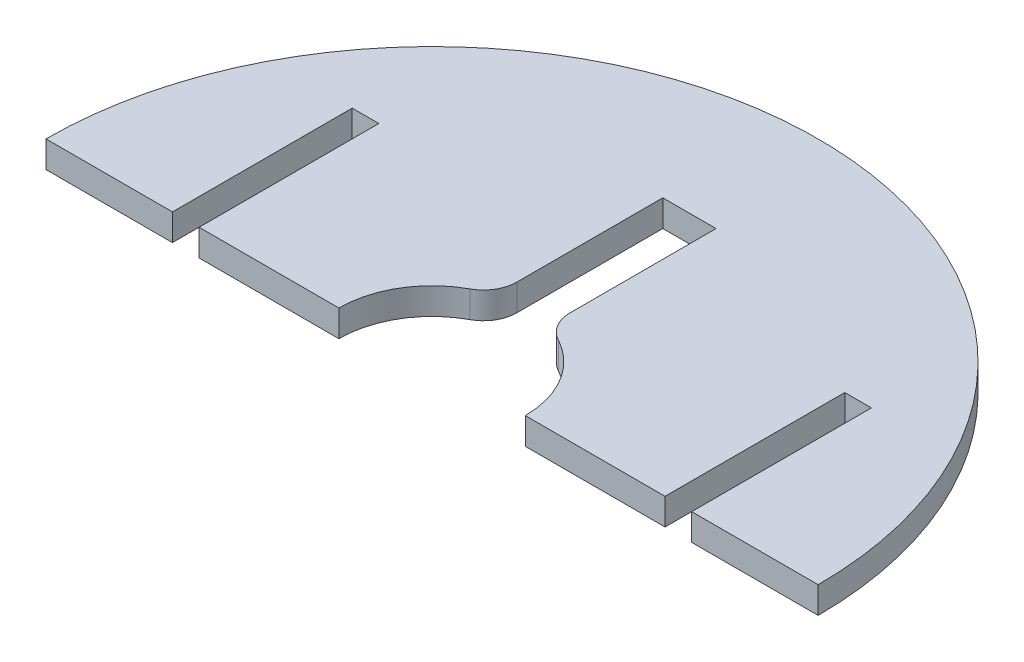
SolidWorks part; units mm, degrees
ref_plane "Front Plane" through (0, 0, 0) normal (0, 0, 1) x (1, 0, 0)
ref_plane "Top Plane" through (0, 0, 0) normal (0, 1, 0) x (1, 0, 0)
ref_plane "Right Plane" through (0, 0, 0) normal (1, 0, 0) x (0, 0, -1)
sketch "Sketch1" plane through (0, 0, 0) normal (0, 1, 0) x (1, 0, 0)
  line L0 (-58, 0) -> (58, 0)
  arc A1 (-58, 0) -> (58, 0) centre (0, 0) cw
  dimension "D1" = 58
extrude "Boss-Extrude1" add sketch "Sketch1" along normal blind 4
sketch "Sketch2" plane through (0, 4, 0) normal (0, 1, 0) x (1, 0, 0)
  line L0 (0, 0) -> (37, 0) construction
  line L1 (35, 0) -> (39, 0)
  line L2 (35, 0) -> (35, 27)
  line L3 (35, 27) -> (39, 27)
  line L4 (39, 0) -> (39, 27)
  line L5 (35, 0) -> (39, 27) construction
  line L6 (35, 27) -> (39, 0) construction
  line L12 (-58, 0) -> (58, 0) construction
  line L13 (0, -2.2) -> (0, 2.2) construction
  line L14 (-35, 27) -> (-39, 27)
  line L15 (-39, 0) -> (-39, 27)
  line L16 (-35, 0) -> (-39, 0)
  line L17 (-35, 0) -> (-35, 27)
  point P0 (37, 0)
  dimension "D1" = 27
  dimension "D2" = 4
  dimension "D3" = 35
extrude "Cut-Extrude1" cut sketch "Sketch2" against normal through all
sketch "Sketch3" plane through (0, 4, 0) normal (0, 1, 0) x (1, 0, 0)
  line L0 (-35, 0) -> (35, 0) construction
  line L1 (-4, 16.7332) -> (-4, 38.6632)
  line L2 (-4, 38.6632) -> (4, 38.6632)
  line L3 (0, 38.6632) -> (0, 0)
  line L4 (4, 16.7332) -> (4, 38.6632)
  line L5 (-14, 0) -> (14, 0)
  arc A0 (-14, 0) -> (-6.6316, 12.3297) centre (0, 0) cw
  arc A1 (-6.6316, 12.3297) -> (-4, 16.7332) centre (-9, 16.7332) ccw
  arc A2 (6.6316, 12.3297) -> (4, 16.7332) centre (9, 16.7332) cw
  arc A3 (14, 0) -> (6.6316, 12.3297) centre (0, 0) ccw
  line M12 (-35, 0) -> (35, 0)
  dimension "D1" = 14
  dimension "D2" = 5
  dimension "D3" = 21.93
  dimension "D4" = 4
extrude "Cut-Extrude2" cut sketch "Sketch3" against normal through all contours A3 A2 L4 L2 L3 M12 | A1 A0 L3 L2 L1 M12
